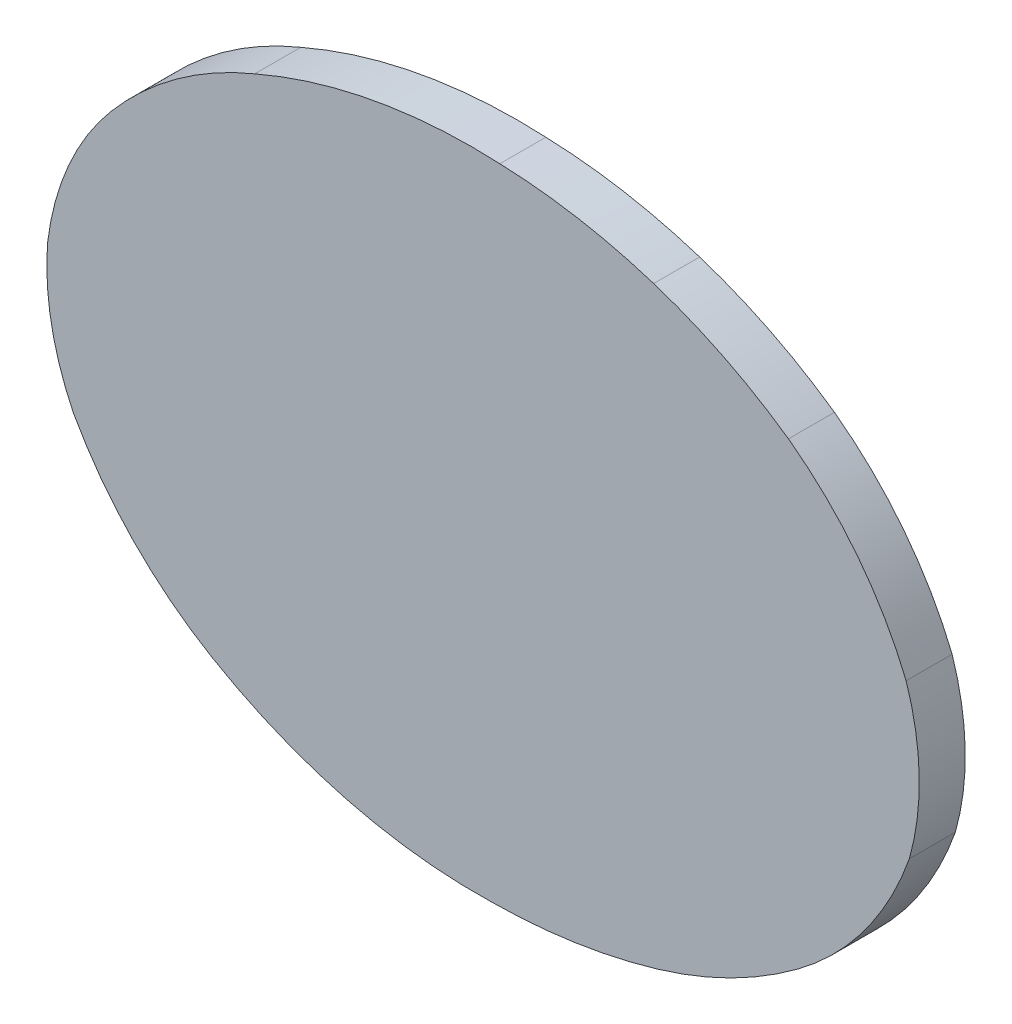
SolidWorks part; units mm, degrees
ref_plane "Front Plane" through (0, 0, 0) normal (0, 0, 1) x (1, 0, 0)
ref_plane "Top Plane" through (0, 0, 0) normal (0, 1, 0) x (1, 0, 0)
ref_plane "Right Plane" through (0, 0, 0) normal (1, 0, 0) x (0, 0, -1)
sketch "Sketch2" plane through (0, 0, 0) normal (0, 0, 1) x (1, 0, 0)
  arc A0 (-13.3262, -24.0128) -> (0.6793, -26.0095) centre (0.3009, 21.4564) ccw
  arc A1 (0.6793, -26.0095) -> (14.5823, -23.9375) centre (0.2777, 24.3658) ccw
  arc A2 (14.5823, -23.9375) -> (26.2276, -18.1061) centre (4.0419, 11.655) ccw
  arc A3 (26.2276, -18.1061) -> (35.1758, -5.9704) centre (10.7223, 2.6936) ccw
  arc A4 (35.1758, -5.9704) -> (34.9249, 5.9975) centre (15.3813, -0.3989) ccw
  arc A5 (34.9249, 5.9975) -> (25.4017, 18.1723) centre (8.4273, -4.917) ccw
  arc A6 (25.4017, 18.1723) -> (14.2292, 23.7276) centre (1.3725, -16.1413) ccw
  arc A7 (1.3785, 25.9665) -> (14.2292, 23.7276) centre (-0.171, -20.9276) cw
  arc A8 (1.3785, 25.9665) -> (-19.0844, 22.2321) centre (-0.929, -19.3211) ccw
  arc A9 (-19.0844, 22.2321) -> (-30.8476, 13.69) centre (-7.504, -6.0856) ccw
  arc A10 (-30.8476, 13.69) -> (-35.8889, 2.1324) centre (-14.1109, -0.4886) ccw
  arc A11 (-35.8889, 2.1324) -> (-33.8531, -8.439) centre (-15.3178, 0.6122) ccw
  arc A12 (-33.8531, -8.439) -> (-22.5701, -20.0102) centre (-6.9795, 6.4787) ccw
  arc A13 (-22.5701, -20.0102) -> (0.6793, -26.0095) centre (-0.492, 17.5011) ccw
  arc A14 (0.6793, -26.0095) -> (14.5823, -23.9375) centre (0.2777, 24.3658) ccw
  arc A15 (14.5823, -23.9375) -> (26.2276, -18.1061) centre (4.4621, 10.8158) ccw
  arc A16 (26.2276, -18.1061) -> (35.1758, -5.9704) centre (10.7223, 2.6936) ccw
extrude "Boss-Extrude1" add sketch "Sketch2" along normal blind 1
sketch "Sketch3" plane through (0, 0, 1) normal (0, 0, 1) x (1, 0, 0)
  arc A26 (-23.5846, -21.7338) -> (0.7142, -28.0092) centre (-0.492, 17.5011) ccw
  arc A27 (0.7142, -28.0092) -> (15.1502, -25.8552) centre (0.2777, 24.3658) ccw
  arc A28 (15.1502, -25.8552) -> (27.4229, -19.7095) centre (4.0419, 11.655) ccw
  arc A29 (27.4229, -19.7095) -> (37.0829, -6.5762) centre (10.7223, 2.6936) ccw
  arc A30 (37.0829, -6.5762) -> (36.8022, 6.6907) centre (15.3813, -0.3989) ccw
  arc A31 (36.8022, 6.6907) -> (26.5677, 19.7974) centre (8.4273, -4.917) ccw
  arc A32 (26.5677, 19.7974) -> (14.8431, 25.6311) centre (1.3725, -16.1413) ccw
  arc A33 (14.8431, 25.6311) -> (1.4625, 27.9648) centre (-0.171, -20.9276) ccw
  arc A34 (1.4625, 27.9648) -> (-19.8636, 24.0743) centre (-0.929, -19.3211) ccw
  arc A35 (-19.8636, 24.0743) -> (-32.3736, 14.9828) centre (-7.504, -6.0856) ccw
  arc A36 (-32.3736, 14.9828) -> (-37.88, 2.3257) centre (-14.1109, -0.4886) ccw
  arc A37 (-37.88, 2.3257) -> (-35.627, -9.3641) centre (-15.3178, 0.6122) ccw
  arc A38 (-35.627, -9.3641) -> (-23.5846, -21.7338) centre (-6.9795, 6.4787) ccw
  arc A39 (-23.5846, -21.7338) -> (0.7142, -28.0092) centre (-0.492, 17.5011) ccw
  arc A40 (0.7142, -28.0092) -> (15.1502, -25.8552) centre (0.2777, 24.3658) ccw
  arc A41 (15.1502, -25.8552) -> (27.4229, -19.7095) centre (4.0419, 11.655) ccw
  arc A42 (27.4229, -19.7095) -> (37.0829, -6.5762) centre (10.7223, 2.6936) ccw
  arc A43 (37.0829, -6.5762) -> (36.8022, 6.6907) centre (15.3813, -0.3989) ccw
  arc A44 (36.8022, 6.6907) -> (26.5677, 19.7974) centre (8.4273, -4.917) ccw
  arc A45 (26.5677, 19.7974) -> (14.8431, 25.6311) centre (1.3725, -16.1413) ccw
  arc A46 (14.8431, 25.6311) -> (1.4625, 27.9648) centre (-0.171, -20.9276) ccw
  arc A47 (1.4625, 27.9648) -> (-19.8636, 24.0743) centre (-0.929, -19.3211) ccw
  arc A48 (-19.8636, 24.0743) -> (-32.3736, 14.9828) centre (-7.504, -6.0856) ccw
  arc A49 (-32.3736, 14.9828) -> (-37.88, 2.3257) centre (-14.1109, -0.4886) ccw
  arc A50 (-37.88, 2.3257) -> (-35.627, -9.3641) centre (-15.3178, 0.6122) ccw
  arc A51 (-35.627, -9.3641) -> (-23.5846, -21.7338) centre (-6.9795, 6.4787) ccw
  arc A65 (-22.5701, -20.0102) -> (0.6793, -26.0095) centre (-0.492, 17.5011) ccw
  arc A66 (0.6793, -26.0095) -> (14.5823, -23.9375) centre (0.2777, 24.3658) ccw
  arc A67 (14.5823, -23.9375) -> (26.2276, -18.1061) centre (4.0419, 11.655) ccw
  arc A68 (26.2276, -18.1061) -> (35.1758, -5.9704) centre (10.7223, 2.6936) ccw
  arc A69 (35.1758, -5.9704) -> (34.9249, 5.9975) centre (15.3813, -0.3989) ccw
  arc A70 (34.9249, 5.9975) -> (25.4017, 18.1723) centre (8.4273, -4.917) ccw
  arc A71 (25.4017, 18.1723) -> (14.2292, 23.7276) centre (1.3725, -16.1413) ccw
  arc A72 (14.2292, 23.7276) -> (1.3785, 25.9665) centre (-0.171, -20.9276) ccw
  arc A73 (1.3785, 25.9665) -> (-19.0844, 22.2321) centre (-0.929, -19.3211) ccw
  arc A74 (-19.0844, 22.2321) -> (-30.8476, 13.69) centre (-7.504, -6.0856) ccw
  arc A75 (-30.8476, 13.69) -> (-35.8889, 2.1324) centre (-14.1109, -0.4886) ccw
  arc A76 (-35.8889, 2.1324) -> (-33.8531, -8.439) centre (-15.3178, 0.6122) ccw
  arc A77 (-33.8531, -8.439) -> (-22.5701, -20.0102) centre (-6.9795, 6.4787) ccw
  arc A78 (-22.5701, -20.0102) -> (0.6793, -26.0095) centre (-0.492, 17.5011) ccw
  arc A79 (0.6793, -26.0095) -> (14.5823, -23.9375) centre (0.2777, 24.3658) ccw
  arc A80 (14.5823, -23.9375) -> (26.2276, -18.1061) centre (4.0419, 11.655) ccw
  arc A81 (26.2276, -18.1061) -> (35.1758, -5.9704) centre (10.7223, 2.6936) ccw
  arc A82 (35.1758, -5.9704) -> (34.9249, 5.9975) centre (15.3813, -0.3989) ccw
  arc A83 (34.9249, 5.9975) -> (25.4017, 18.1723) centre (8.4273, -4.917) ccw
  arc A84 (25.4017, 18.1723) -> (14.2292, 23.7276) centre (1.3725, -16.1413) ccw
  arc A85 (14.2292, 23.7276) -> (1.3785, 25.9665) centre (-0.171, -20.9276) ccw
  arc A86 (1.3785, 25.9665) -> (-19.0844, 22.2321) centre (-0.929, -19.3211) ccw
  arc A87 (-19.0844, 22.2321) -> (-30.8476, 13.69) centre (-7.504, -6.0856) ccw
  arc A88 (-30.8476, 13.69) -> (-35.8889, 2.1324) centre (-14.1109, -0.4886) ccw
  arc A89 (-35.8889, 2.1324) -> (-33.8531, -8.439) centre (-15.3178, 0.6122) ccw
  arc A90 (-33.8531, -8.439) -> (-22.5701, -20.0102) centre (-6.9795, 6.4787) ccw
  dimension "D1" = 2
  dimension "D2" = 0
extrude "Boss-Extrude2" add sketch "Sketch3" against normal blind 2
sketch "Sketch4" plane through (0, 0, -1) normal (0, 0, -1) x (-1, 0, 0)
  arc A26 (23.5846, -21.7338) -> (35.627, -9.3641) centre (6.9795, 6.4787) ccw
  arc A27 (35.627, -9.3641) -> (37.88, 2.3257) centre (15.3178, 0.6122) ccw
  arc A28 (37.88, 2.3257) -> (32.3736, 14.9828) centre (14.1109, -0.4886) ccw
  arc A29 (32.3736, 14.9828) -> (19.8636, 24.0743) centre (7.504, -6.0856) ccw
  arc A30 (19.8636, 24.0743) -> (-1.4625, 27.9648) centre (0.929, -19.3211) ccw
  arc A31 (-1.4625, 27.9648) -> (-14.8431, 25.6311) centre (0.171, -20.9276) ccw
  arc A32 (-14.8431, 25.6311) -> (-26.5677, 19.7974) centre (-1.3725, -16.1413) ccw
  arc A33 (-26.5677, 19.7974) -> (-36.8022, 6.6907) centre (-8.4273, -4.917) ccw
  arc A34 (-36.8022, 6.6907) -> (-37.0829, -6.5762) centre (-15.3813, -0.3989) ccw
  arc A35 (-37.0829, -6.5762) -> (-27.4229, -19.7095) centre (-10.7223, 2.6936) ccw
  arc A36 (-27.4229, -19.7095) -> (-15.1502, -25.8552) centre (-4.0419, 11.655) ccw
  arc A37 (-15.1502, -25.8552) -> (-0.7142, -28.0092) centre (-0.2777, 24.3658) ccw
  arc A38 (-0.7142, -28.0092) -> (23.5846, -21.7338) centre (0.492, 17.5011) ccw
  arc A39 (23.5846, -21.7338) -> (35.627, -9.3641) centre (6.9795, 6.4787) ccw
  arc A40 (35.627, -9.3641) -> (37.88, 2.3257) centre (15.3178, 0.6122) ccw
  arc A41 (37.88, 2.3257) -> (32.3736, 14.9828) centre (14.1109, -0.4886) ccw
  arc A42 (32.3736, 14.9828) -> (19.8636, 24.0743) centre (7.504, -6.0856) ccw
  arc A43 (19.8636, 24.0743) -> (-1.4625, 27.9648) centre (0.929, -19.3211) ccw
  arc A44 (-1.4625, 27.9648) -> (-14.8431, 25.6311) centre (0.171, -20.9276) ccw
  arc A45 (-14.8431, 25.6311) -> (-26.5677, 19.7974) centre (-1.3725, -16.1413) ccw
  arc A46 (-26.5677, 19.7974) -> (-36.8022, 6.6907) centre (-8.4273, -4.917) ccw
  arc A47 (-36.8022, 6.6907) -> (-37.0829, -6.5762) centre (-15.3813, -0.3989) ccw
  arc A48 (-37.0829, -6.5762) -> (-27.4229, -19.7095) centre (-10.7223, 2.6936) ccw
  arc A49 (-27.4229, -19.7095) -> (-15.1502, -25.8552) centre (-4.0419, 11.655) ccw
  arc A50 (-15.1502, -25.8552) -> (-0.7142, -28.0092) centre (-0.2777, 24.3658) ccw
  arc A51 (-0.7142, -28.0092) -> (23.5846, -21.7338) centre (0.492, 17.5011) ccw
  arc A65 (21.5557, -18.2866) -> (32.0787, -7.5146) centre (6.9795, 6.4787) ccw
  arc A66 (32.0787, -7.5146) -> (33.8976, 1.9392) centre (15.3178, 0.6122) ccw
  arc A67 (33.8976, 1.9392) -> (29.3216, 12.3972) centre (14.1109, -0.4886) ccw
  arc A68 (29.3216, 12.3972) -> (18.3056, 20.3898) centre (7.504, -6.0856) ccw
  arc A69 (18.3056, 20.3898) -> (-1.2946, 23.9681) centre (0.929, -19.3211) ccw
  arc A70 (-1.2946, 23.9681) -> (-13.6154, 21.8241) centre (0.171, -20.9276) ccw
  arc A71 (-13.6154, 21.8241) -> (-24.2355, 16.5473) centre (-1.3725, -16.1413) ccw
  arc A72 (-24.2355, 16.5473) -> (-33.0469, 5.3051) centre (-8.4273, -4.917) ccw
  arc A73 (-33.0469, 5.3051) -> (-33.2684, -5.3651) centre (-15.3813, -0.3989) ccw
  arc A74 (-33.2684, -5.3651) -> (-25.0322, -16.5026) centre (-10.7223, 2.6936) ccw
  arc A75 (-25.0322, -16.5026) -> (-14.0144, -22.0198) centre (-4.0419, 11.655) ccw
  arc A76 (-14.0144, -22.0198) -> (-0.6444, -24.0097) centre (-0.2777, 24.3658) ccw
  arc A77 (-0.6444, -24.0097) -> (21.5557, -18.2866) centre (0.492, 17.5011) ccw
  arc A78 (21.5557, -18.2866) -> (32.0787, -7.5146) centre (6.9795, 6.4787) ccw
  arc A79 (32.0787, -7.5146) -> (33.8976, 1.9392) centre (15.3178, 0.6122) ccw
  arc A80 (33.8976, 1.9392) -> (29.3216, 12.3972) centre (14.1109, -0.4886) ccw
  arc A81 (29.3216, 12.3972) -> (18.3056, 20.3898) centre (7.504, -6.0856) ccw
  arc A82 (18.3056, 20.3898) -> (-1.2946, 23.9681) centre (0.929, -19.3211) ccw
  arc A83 (-1.2946, 23.9681) -> (-13.6154, 21.8241) centre (0.171, -20.9276) ccw
  arc A84 (-13.6154, 21.8241) -> (-24.2355, 16.5473) centre (-1.3725, -16.1413) ccw
  arc A85 (-24.2355, 16.5473) -> (-33.0469, 5.3051) centre (-8.4273, -4.917) ccw
  arc A86 (-33.0469, 5.3051) -> (-33.2684, -5.3651) centre (-15.3813, -0.3989) ccw
  arc A87 (-33.2684, -5.3651) -> (-25.0322, -16.5026) centre (-10.7223, 2.6936) ccw
  arc A88 (-25.0322, -16.5026) -> (-14.0144, -22.0198) centre (-4.0419, 11.655) ccw
  arc A89 (-14.0144, -22.0198) -> (-0.6444, -24.0097) centre (-0.2777, 24.3658) ccw
  arc A90 (-0.6444, -24.0097) -> (21.5557, -18.2866) centre (0.492, 17.5011) ccw
  dimension "D1" = 0
  dimension "D2" = 4
extrude "Boss-Extrude3" add sketch "Sketch4" along normal blind 2
